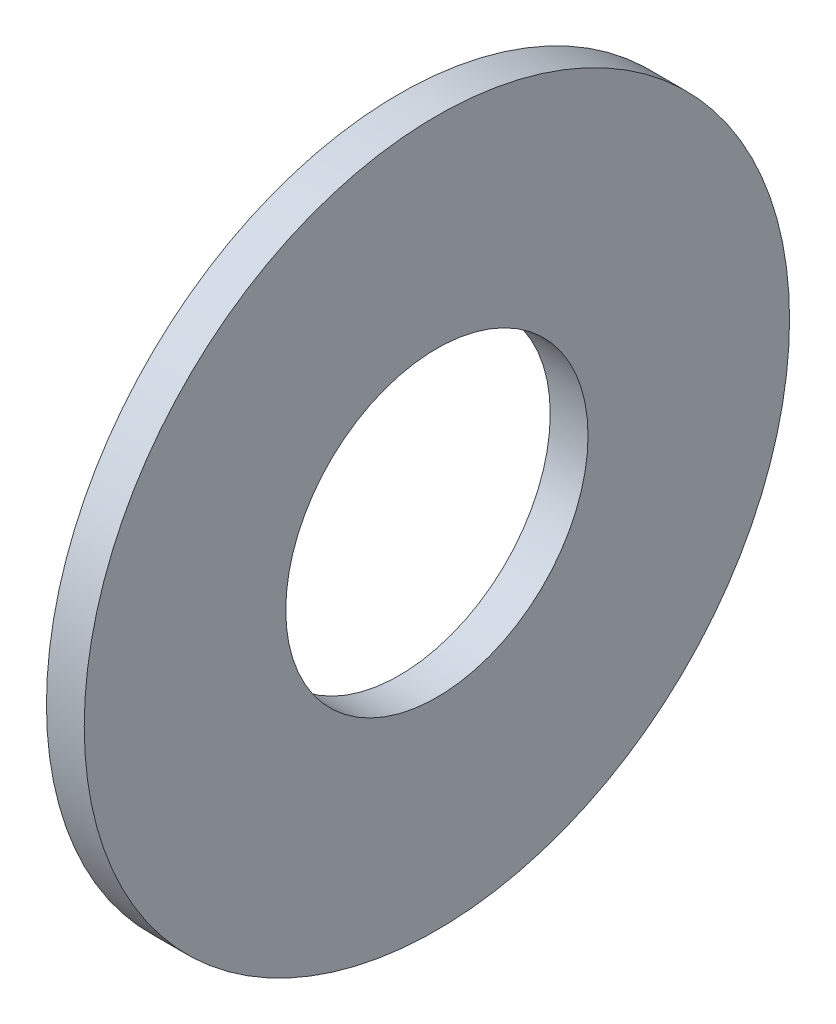
SolidWorks part; units mm, degrees
ref_plane "Front Plane" through (0, 0, 0) normal (0, 0, 1) x (1, 0, 0)
ref_plane "Top Plane" through (0, 0, 0) normal (0, 1, 0) x (1, 0, 0)
ref_plane "Right Plane" through (0, 0, 0) normal (1, 0, 0) x (0, 0, -1)
sketch "Sketch1" plane through (0, 0, 0) normal (1, 0, 0) x (0, 0, -1)
  circle A0 centre (0, 0) radius 3
  circle A1 centre (0, 0) radius 7
  dimension "D1" = 14
  dimension "D2" = 6
extrude "Boss-Extrude1" add sketch "Sketch1" along normal blind 0.75
